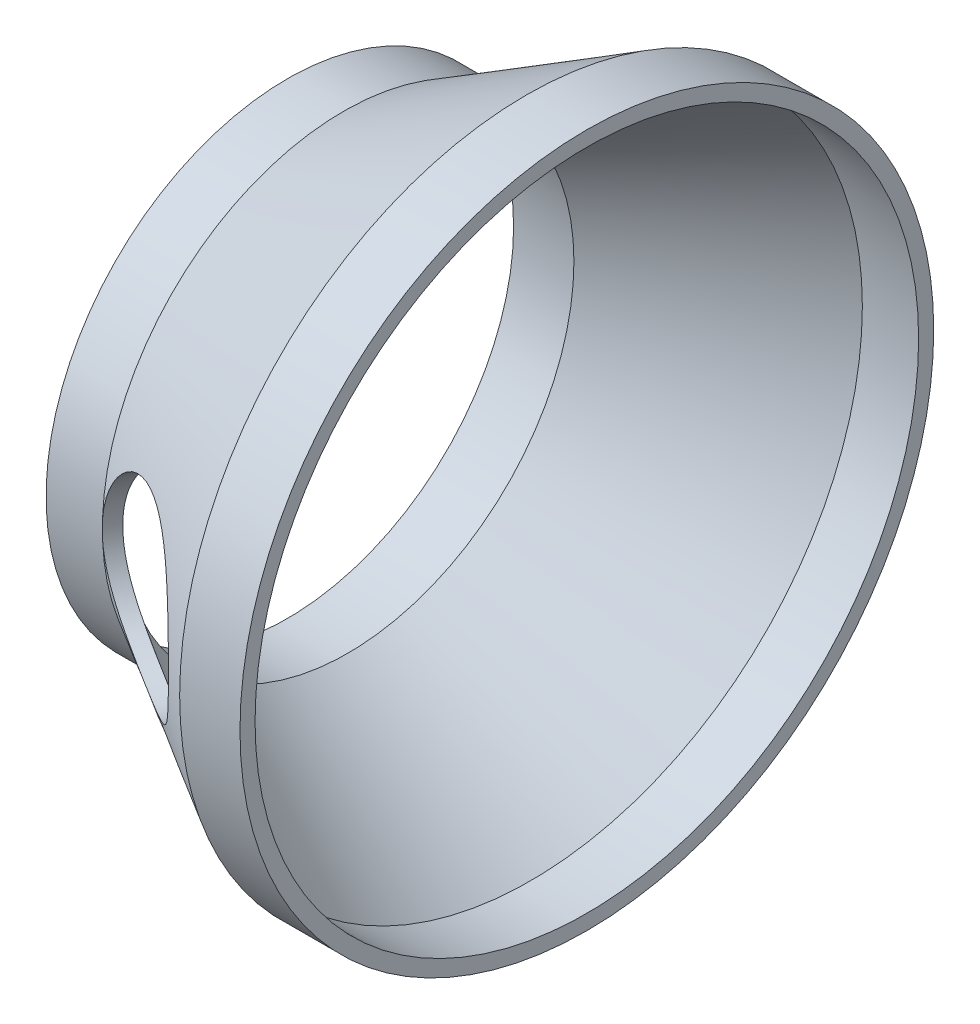
SolidWorks part; units mm, degrees
ref_plane "Front Plane" through (0, 0, 0) normal (0, 0, 1) x (1, 0, 0)
ref_plane "Top Plane" through (0, 0, 0) normal (0, 1, 0) x (1, 0, 0)
ref_plane "Right Plane" through (0, 0, 0) normal (1, 0, 0) x (0, 0, -1)
sketch "Sketch1" plane through (0, 0, 0) normal (0, 0, 1) x (1, 0, 0)
  line L0 (0, 69.85) -> (0, 73.025)
  line L1 (0, 73.025) -> (-12.7, 73.025)
  line L2 (-12.7, 73.025) -> (-51.1948, 50.8)
  line L3 (-51.1948, 50.8) -> (-63.0441, 50.8)
  line L4 (-63.0441, 50.8) -> (-63.0441, 47.625)
  line L5 (-63.0441, 47.625) -> (-50.3441, 47.625)
  line L6 (-50.3441, 47.625) -> (-11.8493, 69.85)
  line L7 (-11.8493, 69.85) -> (0, 69.85)
  line L8 (0, 0) -> (-60.6718, 0) construction
  dimension "D1" = 69.85
  dimension "D2" = 50.8
  dimension "D3" = 3.175
  dimension "D4" = 3.175
  dimension "D5" = 3.175
  dimension "D6" = 30
  dimension "D7" = 12.7
  dimension "D8" = 12.7
revolve "Revolve1" add sketch "Sketch1" angle 360 about L8
ref_plane "Plane1" through (-34.7958, 0, 60.268) normal (-0.5, 0, 0.866) x (0.866, 0, 0.5)
sketch "Sketch2" plane through (-34.7958, 0, 60.268) normal (-0.5, 0, 0.866) x (0.866, 0, 0.5)
  circle A0 centre (0, 0) radius 19.05
  dimension "D1" = 38.1
extrude "Cut-Extrude1" cut sketch "Sketch2" against normal up to next
